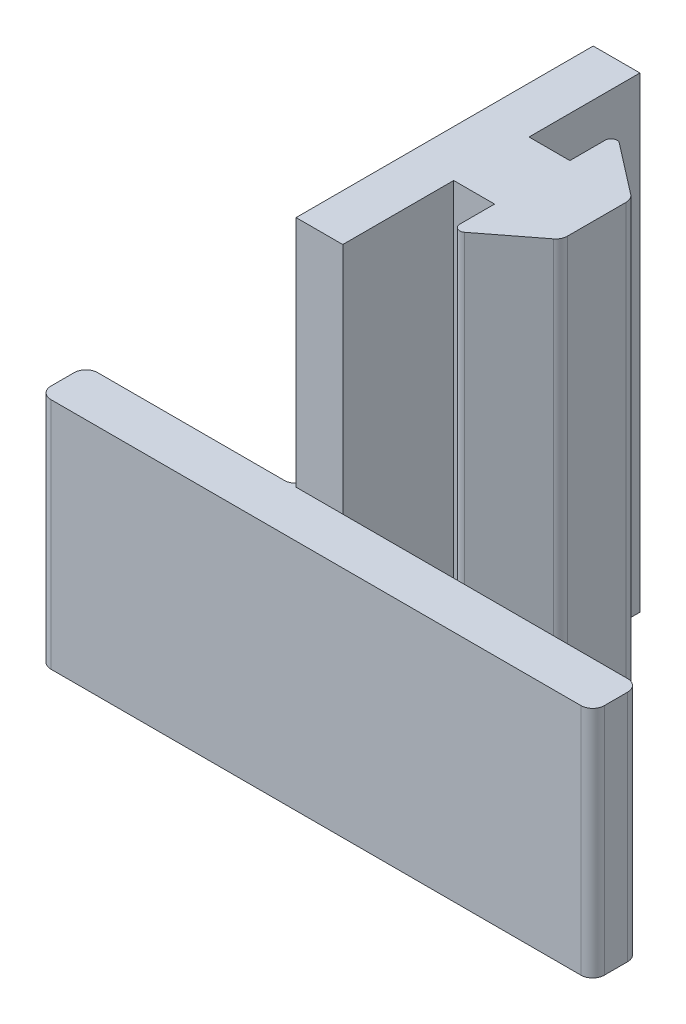
SolidWorks part; units mm, degrees
ref_plane "Front Plane" through (0, 0, 0) normal (0, 0, 1) x (1, 0, 0)
ref_plane "Top Plane" through (0, 0, 0) normal (0, 1, 0) x (1, 0, 0)
ref_plane "Right Plane" through (0, 0, 0) normal (1, 0, 0) x (0, 0, -1)
sketch "Sketch1" plane through (0, 0, 0) normal (0, 1, 0) x (1, 0, 0)
  line L0 (6.5, 10.1595) -> (6.5, 7.1778)
  line L1 (3, 0.6595) -> (28.4, 0.6595)
  line L3 (-4.9999, -3.3405) -> (28.4, -3.3405)
  line L4 (28.4, 0.6595) -> (28.4, -3.3405)
  line L6 (-1, 0.6595) -> (-1, 26.1095)
  line L7 (-1, 26.1095) -> (3, 26.1095)
  line L8 (3, 0.6595) -> (3, 10.1595)
  line L9 (3, 16.6095) -> (6.5, 16.6095)
  line L11 (3, 10.1595) -> (6.5, 10.1595)
  line L14 (6.5, 19.6413) -> (6.5, 16.6095)
  line L19 (3, 16.6095) -> (3, 26.1095)
  line L21 (7.3057, 20.0369) -> (11.6114, 16.7098)
  line L25 (12, 15.9185) -> (12, 10.9006)
  line L26 (7.3057, 6.7821) -> (11.6114, 10.1093)
  line L27 (12, 13.4095) -> (-1, 13.4095) construction
  line L29 (-1, 0.6595) -> (-19, 0.6595)
  line L31 (-4.9999, -3.3405) -> (-19, -3.3405)
  line L32 (-19, 0.6595) -> (-19, -3.3405)
  arc A0 (7.3057, 20.0369) -> (6.5, 19.6413) centre (7, 19.6413) ccw
  arc A1 (6.5, 7.1778) -> (7.3057, 6.7821) centre (7, 7.1778) ccw
  arc A2 (11.6114, 16.7098) -> (12, 15.9185) centre (11, 15.9185) cw
  arc A3 (11.6114, 10.1093) -> (12, 10.9006) centre (11, 10.9006) ccw
  point P0 (4.75, 10.1595)
  point P24 (12, 16.4095)
  dimension "D6" = 0.5
  dimension "D8" = 1
  dimension "D1" = 25.45
  dimension "D2" = 6.45
  dimension "D3" = 12.7
  dimension "D4" = 4
  dimension "D5" = 3.5
  dimension "D7" = 5.5
  dimension "D9" = 25.4
  dimension "D10" = 18
  dimension "D11" = 4
  dimension "D12" = 9.5
extrude "Main-Extrude" add sketch "Sketch1" along normal blind 40
sketch "Sketch4" plane through (0, 0, 3.3405) normal (0, 0, 1) x (1, 0, 0)
  line L0 (28.4, 40) -> (28.4, 0) construction
  line L1 (-19, 40) -> (28.4, 40)
  line L2 (-19, 40) -> (-19, 20)
  line L3 (-19, 20) -> (28.4, 20)
  line L4 (28.4, 40) -> (28.4, 20)
  dimension "D1" = 20
extrude "Cut-Extrude1" cut sketch "Sketch4" against normal up to vertex
fillet "Fillet1" radius 1 3 edges at (-19, 10, 3.3405) (28.4, 10, -0.6595) (28.4, 10, 3.3405)
fillet "Fillet2" radius 1 1 edges at (-19, 10, -0.6595)
fillet "Fillet3" radius 1 1 edges at (-1, 10, -0.6595)
